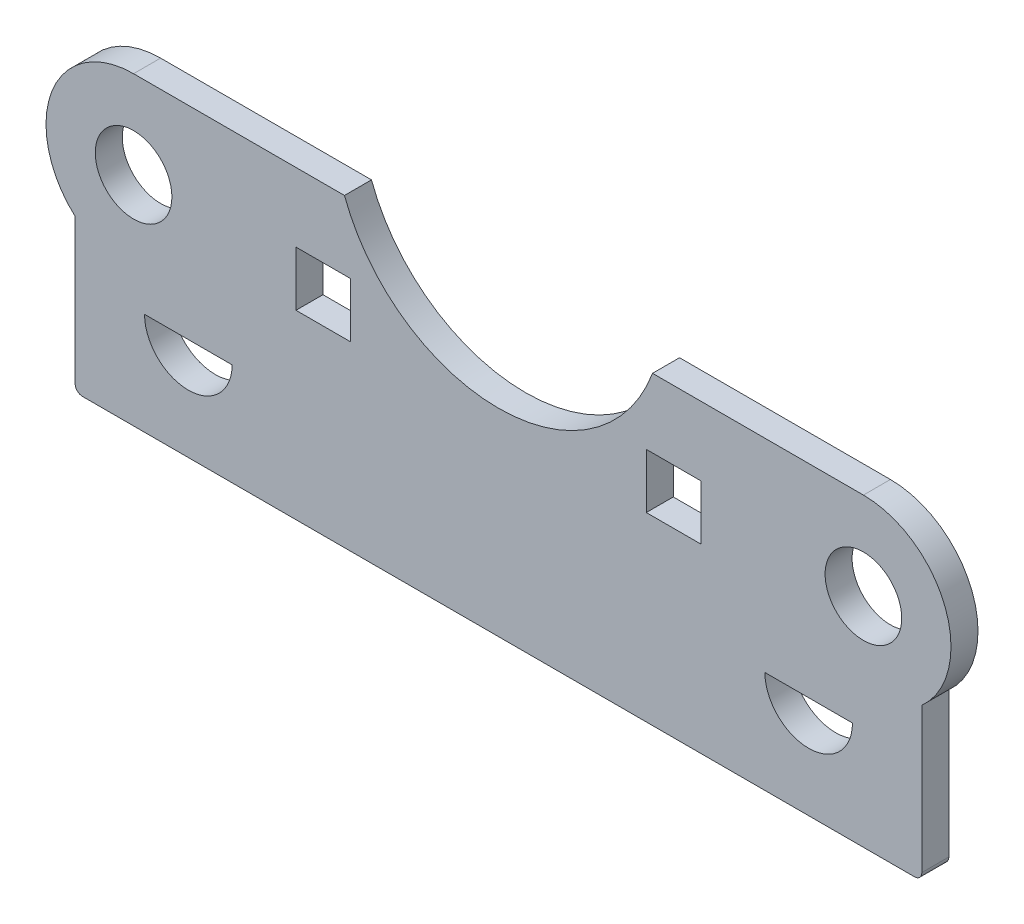
SolidWorks part; units mm, degrees
ref_plane "Front Plane" through (0, 0, 0) normal (0, 0, 1) x (1, 0, 0)
ref_plane "Top Plane" through (0, 0, 0) normal (0, 1, 0) x (1, 0, 0)
ref_plane "Right Plane" through (0, 0, 0) normal (1, 0, 0) x (0, 0, -1)
sketch "Sketch1" plane through (0, 0, 0) normal (0, 0, 1) x (1, 0, 0)
  line L0 (-2743.2, -731.52) -> (-2743.2, -227.1845)
  line L1 (203.2, -731.52) -> (203.2, -227.1845)
  line L2 (-2197.1, -401.32) -> (-2501.9, -401.32)
  line L8 (-1784.35, 64.77) -> (-1974.85, 64.77)
  line L9 (-1784.35, 64.77) -> (-1784.35, -125.73)
  line L10 (-1784.35, -125.73) -> (-1974.85, -125.73)
  line L11 (-1974.85, 64.77) -> (-1974.85, -125.73)
  line L12 (-1784.35, 64.77) -> (-1974.85, -125.73) construction
  line L13 (-1784.35, -125.73) -> (-1974.85, 64.77) construction
  line L14 (-565.15, 64.77) -> (-755.65, 64.77)
  line L15 (-565.15, 64.77) -> (-565.15, -125.73)
  line L16 (-565.15, -125.73) -> (-755.65, -125.73)
  line L17 (-755.65, 64.77) -> (-755.65, -125.73)
  line L18 (-565.15, 64.77) -> (-755.65, -125.73) construction
  line L19 (-565.15, -125.73) -> (-755.65, 64.77) construction
  line L21 (203.2, -756.92) -> (-2540, -756.92)
  line L22 (-2540, -756.92) -> (-2717.8, -756.92)
  line L28 (-2540, 304.8) -> (-1806.0604, 304.8)
  line L32 (-733.9396, 304.8) -> (0, 304.8)
  line L34 (-38.1, -401.32) -> (-342.9, -401.32)
  circle A0 centre (-2540, 0) radius 133.35
  circle A1 centre (0, 0) radius 133.35
  arc A2 (-2540, 304.8) -> (-2743.2, -227.1845) centre (-2540, 0) ccw
  arc A3 (203.2, -227.1845) -> (0, 304.8) centre (0, 0) ccw
  circle A4 centre (-1879.6, -30.48) radius 88.9
  circle A5 centre (-660.4, -30.48) radius 88.9
  arc A6 (-1806.0604, 304.8) -> (-733.9396, 304.8) centre (-1270, 502.92) ccw
  arc A7 (203.2, -731.52) -> (177.8, -756.92) centre (177.8, -731.52) cw
  arc A8 (-2717.8, -756.92) -> (-2743.2, -731.52) centre (-2717.8, -731.52) cw
  arc A11 (-2501.9, -401.32) -> (-2197.1, -401.32) centre (-2349.5, -401.32) ccw
  arc A12 (-342.9, -401.32) -> (-38.1, -401.32) centre (-190.5, -401.32) ccw
  dimension "D2" = 304.8
  dimension "D3" = 304.8
  dimension "D1" = 25.4
extrude "Boss-Extrude1" add sketch "Sketch1" against normal blind 93.98 contours A8 L22 L21 A7 L1 A3 L32 A6 L28 A2 L0 A12 L34 A11 L2 A1 A0 L17 L14 L15 L16 L11 L8 L9 L10
ref_plane "Plane1" through (-1784.35, 64.77, 0) normal (-1, 0, 0) x (0, 0, 1)
